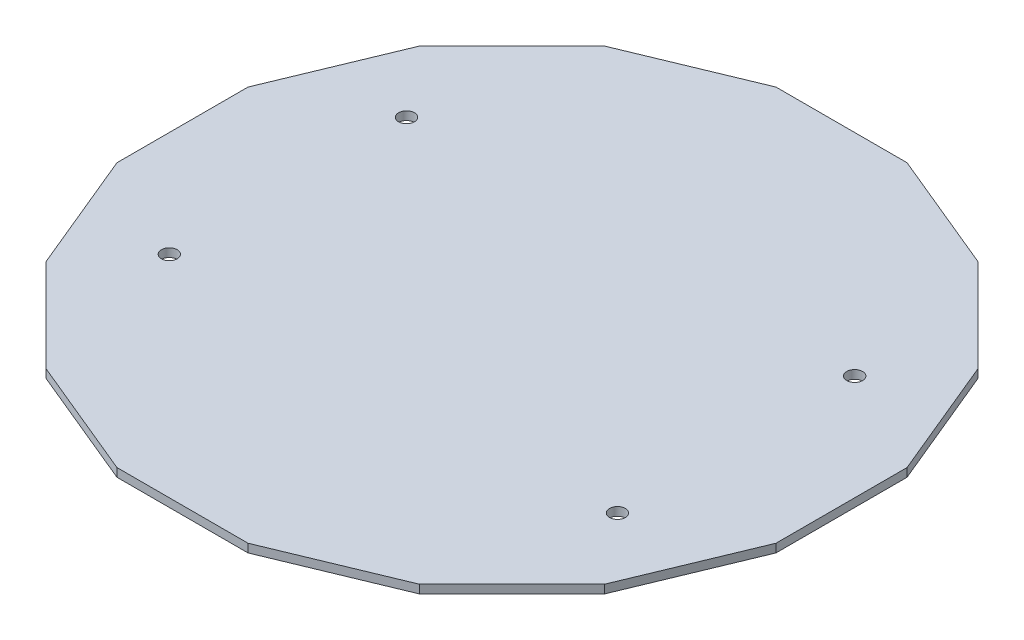
SolidWorks part; units mm, degrees
ref_plane "Front Plane" through (0, 0, 0) normal (0, 0, 1) x (1, 0, 0)
ref_plane "Top Plane" through (0, 0, 0) normal (0, 1, 0) x (1, 0, 0)
ref_plane "Right Plane" through (0, 0, 0) normal (1, 0, 0) x (0, 0, -1)
sketch "Sketch1" plane through (0, 0, 0) normal (0, 1, 0) x (1, 0, 0)
  line L1 (62.5, 12.432) -> (52.9849, 35.4034)
  line L2 (52.9849, 35.4034) -> (35.4034, 52.9849)
  line L3 (35.4034, 52.9849) -> (12.432, 62.5)
  line L4 (12.432, 62.5) -> (-12.432, 62.5)
  line L5 (-12.432, 62.5) -> (-35.4034, 52.9849)
  line L6 (-35.4034, 52.9849) -> (-52.9849, 35.4034)
  line L7 (-52.9849, 35.4034) -> (-62.5, 12.432)
  line L8 (-62.5, 12.432) -> (-62.5, -12.432)
  line L9 (-62.5, -12.432) -> (-52.9849, -35.4034)
  line L10 (-52.9849, -35.4034) -> (-35.4034, -52.9849)
  line L11 (-35.4034, -52.9849) -> (-12.432, -62.5)
  line L12 (-12.432, -62.5) -> (12.432, -62.5)
  line L13 (12.432, -62.5) -> (35.4034, -52.9849)
  line L14 (35.4034, -52.9849) -> (52.9849, -35.4034)
  line L15 (52.9849, -35.4034) -> (62.5, -12.432)
  line L16 (62.5, -12.432) -> (62.5, 12.432)
  circle A0 centre (0, 0) radius 62.5 construction
  dimension "D1" = 125
extrude "Boss-Extrude1" add sketch "Sketch1" along normal blind 1.6
sketch "Sketch2" plane through (0, 0, 0) normal (0, -1, 0) x (1, 0, 0)
  line L0 (-7.5, 62.5) -> (-3.3143, 51)
  line L1 (-12.432, 62.5) -> (12.432, 62.5) construction
  line L2 (-3.3143, 51) -> (3.3143, 51)
  line L3 (3.3143, 51) -> (7.5, 62.5)
  line L4 (7.5, 62.5) -> (9.0963, 62.5)
  line L5 (9.0963, 62.5) -> (4.3647, 49.5)
  line L6 (4.3647, 49.5) -> (-4.3647, 49.5)
  line L7 (-4.3647, 49.5) -> (-9.0963, 62.5)
  line L8 (-9.0963, 62.5) -> (-7.5, 62.5)
  line L131 (15.5139, 61.2235) -> (16.9886, 60.6126)
  line L132 (16.9886, 60.6126) -> (16.4548, 48.3862)
  line L133 (16.4548, 48.3862) -> (22.5789, 45.8495)
  line L134 (22.5789, 45.8495) -> (30.8468, 54.8723)
  line L135 (30.8468, 54.8723) -> (32.3216, 54.2615)
  line L136 (32.3216, 54.2615) -> (22.9752, 44.0618)
  line L137 (22.9752, 44.0618) -> (14.9104, 47.4023)
  line L138 (14.9104, 47.4023) -> (15.5139, 61.2235)
  line L139 (37.7621, 50.6262) -> (38.8909, 49.4975)
  line L140 (38.8909, 49.4975) -> (33.7189, 38.406)
  line L141 (33.7189, 38.406) -> (38.406, 33.7189)
  line L142 (38.406, 33.7189) -> (49.4975, 38.8909)
  line L143 (49.4975, 38.8909) -> (50.6262, 37.7621)
  line L144 (50.6262, 37.7621) -> (38.0881, 31.9155)
  line L145 (38.0881, 31.9155) -> (31.9155, 38.0881)
  line L146 (31.9155, 38.0881) -> (37.7621, 50.6262)
  line L147 (54.2615, 32.3216) -> (54.8723, 30.8468)
  line L148 (54.8723, 30.8468) -> (45.8495, 22.5789)
  line L149 (45.8495, 22.5789) -> (48.3862, 16.4548)
  line L150 (48.3862, 16.4548) -> (60.6126, 16.9886)
  line L151 (60.6126, 16.9886) -> (61.2235, 15.5139)
  line L152 (61.2235, 15.5139) -> (47.4023, 14.9104)
  line L153 (47.4023, 14.9104) -> (44.0618, 22.9752)
  line L154 (44.0618, 22.9752) -> (54.2615, 32.3216)
  line L155 (62.5, 9.0963) -> (62.5, 7.5)
  line L156 (62.5, 7.5) -> (51, 3.3143)
  line L157 (51, 3.3143) -> (51, -3.3143)
  line L158 (51, -3.3143) -> (62.5, -7.5)
  line L167 (62.5, -7.5) -> (62.5, -9.0963)
  line L184 (62.5, -9.0963) -> (49.5, -4.3647)
  line L185 (49.5, -4.3647) -> (49.5, 4.3647)
  line L186 (49.5, 4.3647) -> (62.5, 9.0963)
  line L187 (61.2235, -15.5139) -> (60.6126, -16.9886)
  line L188 (60.6126, -16.9886) -> (48.3862, -16.4548)
  line L189 (48.3862, -16.4548) -> (45.8495, -22.5789)
  line L190 (45.8495, -22.5789) -> (54.8723, -30.8468)
  line L191 (54.8723, -30.8468) -> (54.2615, -32.3216)
  line L192 (54.2615, -32.3216) -> (44.0618, -22.9752)
  line L193 (44.0618, -22.9752) -> (47.4023, -14.9104)
  line L194 (47.4023, -14.9104) -> (61.2235, -15.5139)
  line L195 (50.6262, -37.7621) -> (49.4975, -38.8909)
  line L196 (49.4975, -38.8909) -> (38.406, -33.7189)
  line L197 (38.406, -33.7189) -> (33.7189, -38.406)
  line L198 (33.7189, -38.406) -> (38.8909, -49.4975)
  line L199 (38.8909, -49.4975) -> (37.7621, -50.6262)
  line L200 (37.7621, -50.6262) -> (31.9155, -38.0881)
  line L201 (31.9155, -38.0881) -> (38.0881, -31.9155)
  line L202 (38.0881, -31.9155) -> (50.6262, -37.7621)
  line L203 (32.3216, -54.2615) -> (30.8468, -54.8723)
  line L204 (30.8468, -54.8723) -> (22.5789, -45.8495)
  line L205 (22.5789, -45.8495) -> (16.4548, -48.3862)
  line L206 (16.4548, -48.3862) -> (16.9886, -60.6126)
  line L207 (16.9886, -60.6126) -> (15.5139, -61.2235)
  line L208 (15.5139, -61.2235) -> (14.9104, -47.4023)
  line L209 (14.9104, -47.4023) -> (22.9752, -44.0618)
  line L210 (22.9752, -44.0618) -> (32.3216, -54.2615)
  line L211 (9.0963, -62.5) -> (7.5, -62.5)
  line L212 (7.5, -62.5) -> (3.3143, -51)
  line L213 (3.3143, -51) -> (-3.3143, -51)
  line L214 (-3.3143, -51) -> (-7.5, -62.5)
  line L215 (-7.5, -62.5) -> (-9.0963, -62.5)
  line L216 (-9.0963, -62.5) -> (-4.3647, -49.5)
  line L217 (-4.3647, -49.5) -> (4.3647, -49.5)
  line L218 (4.3647, -49.5) -> (9.0963, -62.5)
  line L219 (-15.5139, -61.2235) -> (-16.9886, -60.6126)
  line L220 (-16.9886, -60.6126) -> (-16.4548, -48.3862)
  line L221 (-16.4548, -48.3862) -> (-22.5789, -45.8495)
  line L222 (-22.5789, -45.8495) -> (-30.8468, -54.8723)
  line L223 (-30.8468, -54.8723) -> (-32.3216, -54.2615)
  line L224 (-32.3216, -54.2615) -> (-22.9752, -44.0618)
  line L225 (-22.9752, -44.0618) -> (-14.9104, -47.4023)
  line L226 (-14.9104, -47.4023) -> (-15.5139, -61.2235)
  line L227 (-37.7621, -50.6262) -> (-38.8909, -49.4975)
  line L228 (-38.8909, -49.4975) -> (-33.7189, -38.406)
  line L229 (-33.7189, -38.406) -> (-38.406, -33.7189)
  line L230 (-38.406, -33.7189) -> (-49.4975, -38.8909)
  line L231 (-49.4975, -38.8909) -> (-50.6262, -37.7621)
  line L232 (-50.6262, -37.7621) -> (-38.0881, -31.9155)
  line L233 (-38.0881, -31.9155) -> (-31.9155, -38.0881)
  line L234 (-31.9155, -38.0881) -> (-37.7621, -50.6262)
  line L235 (-54.2615, -32.3216) -> (-54.8723, -30.8468)
  line L236 (-54.8723, -30.8468) -> (-45.8495, -22.5789)
  line L237 (-45.8495, -22.5789) -> (-48.3862, -16.4548)
  line L238 (-48.3862, -16.4548) -> (-60.6126, -16.9886)
  line L239 (-60.6126, -16.9886) -> (-61.2235, -15.5139)
  line L240 (-61.2235, -15.5139) -> (-47.4023, -14.9104)
  line L241 (-47.4023, -14.9104) -> (-44.0618, -22.9752)
  line L242 (-44.0618, -22.9752) -> (-54.2615, -32.3216)
  line L243 (-62.5, -9.0963) -> (-62.5, -7.5)
  line L244 (-62.5, -7.5) -> (-51, -3.3143)
  line L245 (-51, -3.3143) -> (-51, 3.3143)
  line L246 (-51, 3.3143) -> (-62.5, 7.5)
  line L247 (-62.5, 7.5) -> (-62.5, 9.0963)
  line L248 (-62.5, 9.0963) -> (-49.5, 4.3647)
  line L249 (-49.5, 4.3647) -> (-49.5, -4.3647)
  line L250 (-49.5, -4.3647) -> (-62.5, -9.0963)
  line L251 (-61.2235, 15.5139) -> (-60.6126, 16.9886)
  line L252 (-60.6126, 16.9886) -> (-48.3862, 16.4548)
  line L253 (-48.3862, 16.4548) -> (-45.8495, 22.5789)
  line L254 (-45.8495, 22.5789) -> (-54.8723, 30.8468)
  line L255 (-54.8723, 30.8468) -> (-54.2615, 32.3216)
  line L256 (-54.2615, 32.3216) -> (-44.0618, 22.9752)
  line L257 (-44.0618, 22.9752) -> (-47.4023, 14.9104)
  line L258 (-47.4023, 14.9104) -> (-61.2235, 15.5139)
  line L259 (-50.6262, 37.7621) -> (-49.4975, 38.8909)
  line L260 (-49.4975, 38.8909) -> (-38.406, 33.7189)
  line L261 (-38.406, 33.7189) -> (-33.7189, 38.406)
  line L262 (-33.7189, 38.406) -> (-38.8909, 49.4975)
  line L263 (-38.8909, 49.4975) -> (-37.7621, 50.6262)
  line L264 (-37.7621, 50.6262) -> (-31.9155, 38.0881)
  line L265 (-31.9155, 38.0881) -> (-38.0881, 31.9155)
  line L266 (-38.0881, 31.9155) -> (-50.6262, 37.7621)
  line L267 (-32.3216, 54.2615) -> (-30.8468, 54.8723)
  line L268 (-30.8468, 54.8723) -> (-22.5789, 45.8495)
  line L269 (-22.5789, 45.8495) -> (-16.4548, 48.3862)
  line L270 (-16.4548, 48.3862) -> (-16.9886, 60.6126)
  line L271 (-16.9886, 60.6126) -> (-15.5139, 61.2235)
  line L272 (-15.5139, 61.2235) -> (-14.9104, 47.4023)
  line L273 (-14.9104, 47.4023) -> (-22.9752, 44.0618)
  line L274 (-22.9752, 44.0618) -> (-32.3216, 54.2615)
  point P4 (0, 51)
  point P11 (0, 49.5)
  point P136 (0, 0)
  point P138 (0, 0)
  dimension "D6" = 16
  dimension "D1" = 1.5
  dimension "D2" = 1.5
  dimension "D3" = 15
  dimension "D4" = 40
  dimension "D5" = 11.5
extrude "Boss-Extrude5" [suppressed] add sketch "Sketch2" along normal blind 6
sketch "Sketch6" plane through (0, 1.6, 0) normal (0, 1, 0) x (1, 0, 0)
  line L1 (-42.5, -22.5) -> (42.5, -22.5) construction
  line L2 (-42.5, -22.5) -> (-42.5, 22.5) construction
  line L3 (-42.5, 22.5) -> (42.5, 22.5) construction
  line L4 (42.5, -22.5) -> (42.5, 22.5) construction
  line L5 (-42.5, -22.5) -> (42.5, 22.5) construction
  line L6 (-42.5, 22.5) -> (42.5, -22.5) construction
  circle A0 centre (-42.5, 22.5) radius 1.5
  circle A1 centre (-42.5, -22.5) radius 1.5
  circle A2 centre (42.5, -22.5) radius 1.5
  circle A3 centre (42.5, 22.5) radius 1.5
  point P0 (0, 0)
  dimension "D3" = 3
  dimension "D1" = 85
  dimension "D2" = 45
extrude "Cut-Extrude2" cut sketch "Sketch6" against normal up to surface (1.6 mm away) up to face at (0, 0, 0)
sketch "Sketch17" [suppressed] plane through (0, -6, 0) normal (0, -1, 0) x (1, 0, 0)
  line L1 (-9.8462, 49.5) -> (-28.0395, 41.9641)
  line L2 (-28.0395, 41.9641) -> (-41.9641, 28.0395)
  line L3 (-41.9641, 28.0395) -> (-49.5, 9.8462)
  line L4 (-49.5, 9.8462) -> (-49.5, -9.8462)
  line L5 (-49.5, -9.8462) -> (-41.9641, -28.0395)
  line L6 (-41.9641, -28.0395) -> (-28.0395, -41.9641)
  line L7 (-28.0395, -41.9641) -> (-9.8462, -49.5)
  line L8 (-9.8462, -49.5) -> (9.8462, -49.5)
  line L9 (9.8462, -49.5) -> (28.0395, -41.9641)
  line L10 (28.0395, -41.9641) -> (41.9641, -28.0395)
  line L11 (41.9641, -28.0395) -> (49.5, -9.8462)
  line L12 (49.5, -9.8462) -> (49.5, 9.8462)
  line L13 (49.5, 9.8462) -> (41.9641, 28.0395)
  line L14 (41.9641, 28.0395) -> (28.0395, 41.9641)
  line L15 (28.0395, 41.9641) -> (9.8462, 49.5)
  line L16 (9.8462, 49.5) -> (-9.8462, 49.5)
  line L18 (-49.5, -4.3647) -> (-49.5, 4.3647) construction
  line L20 (-10.1445, 51) -> (-28.8892, 43.2357)
  line L21 (-28.8892, 43.2357) -> (-43.2357, 28.8892)
  line L22 (-43.2357, 28.8892) -> (-51, 10.1445)
  line L23 (-51, 10.1445) -> (-51, -10.1445)
  line L24 (-51, -10.1445) -> (-43.2357, -28.8892)
  line L25 (-43.2357, -28.8892) -> (-28.8892, -43.2357)
  line L26 (-28.8892, -43.2357) -> (-10.1445, -51)
  line L27 (-10.1445, -51) -> (10.1445, -51)
  line L28 (10.1445, -51) -> (28.8892, -43.2357)
  line L29 (28.8892, -43.2357) -> (43.2357, -28.8892)
  line L30 (43.2357, -28.8892) -> (51, -10.1445)
  line L31 (51, -10.1445) -> (51, 10.1445)
  line L32 (51, 10.1445) -> (43.2357, 28.8892)
  line L33 (43.2357, 28.8892) -> (28.8892, 43.2357)
  line L34 (28.8892, 43.2357) -> (10.1445, 51)
  line L35 (10.1445, 51) -> (-10.1445, 51)
  line L36 (-51, 3.3143) -> (-51, -3.3143) construction
  circle A0 centre (0, 0) radius 49.5 construction
  circle A1 centre (0, 0) radius 51 construction
extrude "Boss-Extrude9" [suppressed] add sketch "Sketch17" against normal up to surface (6 mm away)
sketch "Sketch16" [suppressed] plane through (0, -6, 0) normal (0, -1, 0) x (1, 0, 0)
  line L0 (-49.5, 9.8462) -> (-41.9641, 28.0395) construction
  line L1 (-43.8477, 19.2462) -> (-40.356, 19.7059)
  line L2 (-40.356, 19.7059) -> (-39.0083, 22.9597)
  line L3 (-39.0083, 22.9597) -> (-41.1523, 25.7538)
  line L4 (-41.1523, 25.7538) -> (-44.644, 25.2941)
  line L5 (-44.644, 25.2941) -> (-45.9917, 22.0403)
  line L6 (-45.9917, 22.0403) -> (-43.8477, 19.2462)
  line L7 (0, -0.88) -> (0, 0.88) construction
  line L8 (45.9917, 22.0403) -> (43.8477, 19.2462)
  line L9 (44.644, 25.2941) -> (45.9917, 22.0403)
  line L10 (41.1523, 25.7538) -> (44.644, 25.2941)
  line L11 (39.0083, 22.9597) -> (41.1523, 25.7538)
  line L12 (40.356, 19.7059) -> (39.0083, 22.9597)
  line L13 (43.8477, 19.2462) -> (40.356, 19.7059)
  line L14 (0.88, 0) -> (-0.88, 0) construction
  line L15 (44.644, -25.2941) -> (45.9917, -22.0403)
  line L16 (41.1523, -25.7538) -> (44.644, -25.2941)
  line L17 (39.0083, -22.9597) -> (41.1523, -25.7538)
  line L18 (40.356, -19.7059) -> (39.0083, -22.9597)
  line L19 (43.8477, -19.2462) -> (40.356, -19.7059)
  line L20 (45.9917, -22.0403) -> (43.8477, -19.2462)
  line L21 (-45.9917, -22.0403) -> (-43.8477, -19.2462)
  line L22 (-44.644, -25.2941) -> (-45.9917, -22.0403)
  line L23 (-41.1523, -25.7538) -> (-44.644, -25.2941)
  line L24 (-39.0083, -22.9597) -> (-41.1523, -25.7538)
  line L25 (-40.356, -19.7059) -> (-39.0083, -22.9597)
  line L26 (-43.8477, -19.2462) -> (-40.356, -19.7059)
  circle A0 centre (-42.5, 22.5) radius 3.05 construction
  dimension "D1" = 6.1
extrude "Cut-Extrude5" [suppressed] cut sketch "Sketch16" against normal up to surface (6 mm away)
sketch "Sketch21" [suppressed] plane through (0, 0, 0) normal (0, -1, 0) x (1, 0, 0)
  line L0 (-44.644, 25.2941) -> (-45.9917, 22.0403) construction
  line L1 (-47.1365, 21.8896) -> (-45.4317, 19.6678)
  line L5 (-42.5704, 26.5757) -> (-45.3469, 26.2101)
  line L6 (-45.3469, 26.2101) -> (-47.1365, 21.8896)
  line L7 (-45.9917, 22.0403) -> (-44.9898, 20.7347)
  line L11 (-43.0123, 25.5089) -> (-44.644, 25.2941)
  line L12 (-44.644, 25.2941) -> (-45.9917, 22.0403)
  line L13 (-43.0123, 25.5089) -> (-42.5704, 26.5757)
  line L15 (-43.0123, 25.5089) -> (-41.9641, 28.0395) construction
  line L16 (-44.9898, 20.7347) -> (-45.4317, 19.6678)
  line L17 (-49.5, 9.8462) -> (-44.9898, 20.7347) construction
  line L18 (0, -4.18) -> (0, 4.18) construction
  line L19 (-42.1019, 19.4761) -> (-40.356, 19.7059) [skipped]
  line L20 (-41.9714, 18.4846) -> (-39.6531, 18.7899) [skipped]
  line L21 (-38.7583, 20.9501) -> (-37.8635, 23.1104) [skipped]
  line L22 (-39.6822, 21.3328) -> (-39.0083, 22.9597) [skipped]
  line L23 (-39.0083, 22.9597) -> (-41.1523, 25.7538) [skipped]
  line L24 (-37.8635, 23.1104) -> (-40.7104, 26.8206) [skipped]
  line L25 (43.0123, 25.5089) -> (42.5704, 26.5757)
  line L26 (42.5704, 26.5757) -> (45.3469, 26.2101)
  line L27 (45.3469, 26.2101) -> (47.1365, 21.8896)
  line L28 (47.1365, 21.8896) -> (45.4317, 19.6678)
  line L29 (44.9898, 20.7347) -> (45.4317, 19.6678)
  line L30 (45.9917, 22.0403) -> (44.9898, 20.7347)
  line L31 (44.644, 25.2941) -> (45.9917, 22.0403)
  line L32 (43.0123, 25.5089) -> (44.644, 25.2941)
  line L33 (4.18, 0) -> (-4.18, 0) construction
  line L34 (43.0123, -25.5089) -> (44.644, -25.2941)
  line L35 (44.644, -25.2941) -> (45.9917, -22.0403)
  line L36 (45.9917, -22.0403) -> (44.9898, -20.7347)
  line L37 (44.9898, -20.7347) -> (45.4317, -19.6678)
  line L38 (47.1365, -21.8896) -> (45.4317, -19.6678)
  line L39 (45.3469, -26.2101) -> (47.1365, -21.8896)
  line L40 (42.5704, -26.5757) -> (45.3469, -26.2101)
  line L41 (43.0123, -25.5089) -> (42.5704, -26.5757)
  line L42 (-44.9898, -20.7347) -> (-45.4317, -19.6678)
  line L43 (-43.0123, -25.5089) -> (-42.5704, -26.5757)
  line L44 (-44.644, -25.2941) -> (-45.9917, -22.0403)
  line L45 (-43.0123, -25.5089) -> (-44.644, -25.2941)
  line L46 (-45.9917, -22.0403) -> (-44.9898, -20.7347)
  line L47 (-45.3469, -26.2101) -> (-47.1365, -21.8896)
  line L48 (-42.5704, -26.5757) -> (-45.3469, -26.2101)
  line L49 (-47.1365, -21.8896) -> (-45.4317, -19.6678)
  arc A0 (-42.5814, 26.5492) -> (-45.4208, 19.6943) centre (-42.5, 22.5) ccw construction
  arc A1 (-42.5814, -26.5492) -> (-45.4208, -19.6943) centre (-42.5, -22.5) cw construction
  dimension "D1" = 1
extrude "Boss-Extrude11" [suppressed] add sketch "Sketch21" along normal up to surface (6 mm away)
sketch "Sketch22" [suppressed] plane through (0, 0, 0) normal (0, -1, 0) x (1, 0, 0)
  line L0 (45.9917, 22.0403) -> (44.644, 25.2941) construction
  line L1 (44.644, 25.2941) -> (41.1523, 25.7538)
  line L2 (41.1523, 25.7538) -> (39.0083, 22.9597)
  line L3 (39.0083, 22.9597) -> (40.356, 19.7059)
  line L4 (40.356, 19.7059) -> (43.8477, 19.2462)
  line L5 (43.8477, 19.2462) -> (45.9917, 22.0403)
  line L6 (45.9917, 22.0403) -> (44.644, 25.2941)
  line L7 (0, -4.18) -> (0, 4.18) construction
  line L8 (-45.9917, 22.0403) -> (-44.644, 25.2941)
  line L9 (-43.8477, 19.2462) -> (-45.9917, 22.0403)
  line L10 (-40.356, 19.7059) -> (-43.8477, 19.2462)
  line L11 (-39.0083, 22.9597) -> (-40.356, 19.7059)
  line L12 (-41.1523, 25.7538) -> (-39.0083, 22.9597)
  line L13 (-44.644, 25.2941) -> (-41.1523, 25.7538)
  line L14 (4.18, 0) -> (-4.18, 0) construction
  line L15 (-44.644, -25.2941) -> (-41.1523, -25.7538)
  line L16 (-41.1523, -25.7538) -> (-39.0083, -22.9597)
  line L17 (-39.0083, -22.9597) -> (-40.356, -19.7059)
  line L18 (-40.356, -19.7059) -> (-43.8477, -19.2462)
  line L19 (-43.8477, -19.2462) -> (-45.9917, -22.0403)
  line L20 (-45.9917, -22.0403) -> (-44.644, -25.2941)
  line L21 (45.9917, -22.0403) -> (44.644, -25.2941)
  line L22 (43.8477, -19.2462) -> (45.9917, -22.0403)
  line L23 (40.356, -19.7059) -> (43.8477, -19.2462)
  line L24 (39.0083, -22.9597) -> (40.356, -19.7059)
  line L25 (41.1523, -25.7538) -> (39.0083, -22.9597)
  line L26 (44.644, -25.2941) -> (41.1523, -25.7538)
  circle A0 centre (42.5, 22.5) radius 3.05 construction
  circle A1 centre (42.5, 22.5) radius 1.5
  circle A2 centre (42.5, 22.5) radius 1.5 construction
  circle A3 centre (42.5, -22.5) radius 3.05 construction
  circle A4 centre (42.5, -22.5) radius 1.5
  circle A5 centre (-42.5, 22.5) radius 1.5
  circle A6 centre (-42.5, -22.5) radius 1.5
extrude "Boss-Extrude12" [suppressed] add sketch "Sketch22" along normal blind 2
sketch "Sketch23" [suppressed] plane through (0, -2, 0) normal (0, -1, 0) x (1, 0, 0)
  line L0 (-41.1523, 25.7538) -> (-42.2943, 27.2422)
  line L1 (-43.0123, 25.5089) -> (-41.9641, 28.0395) construction
  line L2 (-43.8477, 19.2462) -> (-45.7078, 19.0014)
  line L3 (-49.5, 9.8462) -> (-44.9898, 20.7347) construction
  line L4 (-43.8477, 19.2462) -> (-40.356, 19.7059) construction
  line L5 (-39.0083, 22.9597) -> (-41.1523, 25.7538) construction
  line L6 (-42.2943, 27.2422) -> (-43.0123, 25.5089)
  line L7 (-43.0123, 25.5089) -> (-41.1523, 25.7538)
  line L8 (-44.9898, 20.7347) -> (-43.8477, 19.2462)
  line L9 (-45.7078, 19.0014) -> (-44.9898, 20.7347)
  line L10 (4.18, 0) -> (-4.18, 0) construction
  line L11 (-43.8477, -19.2462) -> (-45.7078, -19.0014)
  line L12 (-44.9898, -20.7347) -> (-43.8477, -19.2462)
  line L13 (-45.7078, -19.0014) -> (-44.9898, -20.7347)
  line L14 (-42.2943, -27.2422) -> (-43.0123, -25.5089)
  line L15 (-41.1523, -25.7538) -> (-42.2943, -27.2422)
  line L16 (-43.0123, -25.5089) -> (-41.1523, -25.7538)
  line L17 (0, -4.18) -> (0, 4.18) construction
  line L18 (43.0123, -25.5089) -> (41.1523, -25.7538)
  line L19 (41.1523, -25.7538) -> (42.2943, -27.2422)
  line L20 (42.2943, -27.2422) -> (43.0123, -25.5089)
  line L21 (45.7078, -19.0014) -> (44.9898, -20.7347)
  line L22 (44.9898, -20.7347) -> (43.8477, -19.2462)
  line L23 (43.8477, -19.2462) -> (45.7078, -19.0014)
  line L24 (45.7078, 19.0014) -> (44.9898, 20.7347)
  line L25 (44.9898, 20.7347) -> (43.8477, 19.2462)
  line L26 (43.0123, 25.5089) -> (41.1523, 25.7538)
  line L27 (42.2943, 27.2422) -> (43.0123, 25.5089)
  line L28 (43.8477, 19.2462) -> (45.7078, 19.0014)
  line L29 (41.1523, 25.7538) -> (42.2943, 27.2422)
extrude "Boss-Extrude13" [suppressed] add sketch "Sketch23" against normal up to surface (2 mm away)
sketch "Sketch24" [suppressed] plane through (0, 0, 0) normal (0, -1, 0) x (1, 0, 0)
  line L0 (-12.432, 62.5) -> (-15.5139, 61.2235)
  line L1 (-15.5139, 61.2235) -> (-14.98, 48.9971)
  line L2 (-14.98, 48.9971) -> (-10.1445, 51)
  line L3 (-10.1445, 51) -> (-4.9106, 51)
  line L4 (-4.9106, 51) -> (-9.0963, 62.5)
  line L5 (-9.0963, 62.5) -> (-12.432, 62.5)
  line L6 (15.5139, 61.2235) -> (12.432, 62.5)
  line L7 (12.432, 62.5) -> (9.0963, 62.5)
  line L8 (9.0963, 62.5) -> (4.9106, 51)
  line L9 (4.9106, 51) -> (10.1445, 51)
  line L10 (10.1445, 51) -> (14.98, 48.9971)
  line L11 (14.98, 48.9971) -> (15.5139, 61.2235)
  line L12 (37.7621, 50.6262) -> (35.4034, 52.9849)
  line L13 (35.4034, 52.9849) -> (32.3216, 54.2615)
  line L14 (32.3216, 54.2615) -> (24.0537, 45.2386)
  line L15 (24.0537, 45.2386) -> (28.8892, 43.2357)
  line L16 (28.8892, 43.2357) -> (32.5901, 39.5348)
  line L17 (32.5901, 39.5348) -> (37.7621, 50.6262)
  line L18 (54.2615, 32.3216) -> (52.9849, 35.4034)
  line L19 (52.9849, 35.4034) -> (50.6262, 37.7621)
  line L20 (50.6262, 37.7621) -> (39.5348, 32.5901)
  line L21 (39.5348, 32.5901) -> (43.2357, 28.8892)
  line L22 (43.2357, 28.8892) -> (45.2386, 24.0537)
  line L23 (45.2386, 24.0537) -> (54.2615, 32.3216)
  line L24 (62.5, 9.0963) -> (62.5, 12.432)
  line L25 (62.5, 12.432) -> (61.2235, 15.5139)
  line L26 (61.2235, 15.5139) -> (48.9971, 14.98)
  line L27 (48.9971, 14.98) -> (51, 10.1445)
  line L28 (51, 10.1445) -> (51, 4.9106)
  line L29 (51, 4.9106) -> (62.5, 9.0963)
  line L30 (61.2235, -15.5139) -> (62.5, -12.432)
  line L31 (62.5, -12.432) -> (62.5, -9.0963)
  line L32 (62.5, -9.0963) -> (51, -4.9106)
  line L33 (51, -4.9106) -> (51, -10.1445)
  line L34 (51, -10.1445) -> (48.9971, -14.98)
  line L35 (48.9971, -14.98) -> (61.2235, -15.5139)
  line L36 (50.6262, -37.7621) -> (52.9849, -35.4034)
  line L37 (52.9849, -35.4034) -> (54.2615, -32.3216)
  line L38 (54.2615, -32.3216) -> (45.2386, -24.0537)
  line L39 (45.2386, -24.0537) -> (43.2357, -28.8892)
  line L40 (43.2357, -28.8892) -> (39.5348, -32.5901)
  line L41 (39.5348, -32.5901) -> (50.6262, -37.7621)
  line L42 (32.3216, -54.2615) -> (35.4034, -52.9849)
  line L43 (35.4034, -52.9849) -> (37.7621, -50.6262)
  line L44 (37.7621, -50.6262) -> (32.5901, -39.5348)
  line L45 (32.5901, -39.5348) -> (28.8892, -43.2357)
  line L46 (28.8892, -43.2357) -> (24.0537, -45.2386)
  line L47 (24.0537, -45.2386) -> (32.3216, -54.2615)
  line L48 (9.0963, -62.5) -> (12.432, -62.5)
  line L49 (12.432, -62.5) -> (15.5139, -61.2235)
  line L50 (15.5139, -61.2235) -> (14.98, -48.9971)
  line L51 (14.98, -48.9971) -> (10.1445, -51)
  line L52 (10.1445, -51) -> (4.9106, -51)
  line L53 (4.9106, -51) -> (9.0963, -62.5)
  line L54 (-15.5139, -61.2235) -> (-12.432, -62.5)
  line L55 (-12.432, -62.5) -> (-9.0963, -62.5)
  line L56 (-9.0963, -62.5) -> (-4.9106, -51)
  line L57 (-4.9106, -51) -> (-10.1445, -51)
  line L58 (-10.1445, -51) -> (-14.98, -48.9971)
  line L59 (-14.98, -48.9971) -> (-15.5139, -61.2235)
  line L60 (-37.7621, -50.6262) -> (-35.4034, -52.9849)
  line L61 (-35.4034, -52.9849) -> (-32.3216, -54.2615)
  line L62 (-32.3216, -54.2615) -> (-24.0537, -45.2386)
  line L63 (-24.0537, -45.2386) -> (-28.8892, -43.2357)
  line L64 (-28.8892, -43.2357) -> (-32.5901, -39.5348)
  line L65 (-32.5901, -39.5348) -> (-37.7621, -50.6262)
  line L66 (-54.2615, -32.3216) -> (-52.9849, -35.4034)
  line L67 (-52.9849, -35.4034) -> (-50.6262, -37.7621)
  line L68 (-50.6262, -37.7621) -> (-39.5348, -32.5901)
  line L69 (-39.5348, -32.5901) -> (-43.2357, -28.8892)
  line L70 (-43.2357, -28.8892) -> (-45.2386, -24.0537)
  line L71 (-45.2386, -24.0537) -> (-54.2615, -32.3216)
  line L72 (-62.5, -9.0963) -> (-62.5, -12.432)
  line L73 (-62.5, -12.432) -> (-61.2235, -15.5139)
  line L74 (-61.2235, -15.5139) -> (-48.9971, -14.98)
  line L75 (-48.9971, -14.98) -> (-51, -10.1445)
  line L76 (-51, -10.1445) -> (-51, -4.9106)
  line L77 (-51, -4.9106) -> (-62.5, -9.0963)
  line L78 (-61.2235, 15.5139) -> (-62.5, 12.432)
  line L79 (-62.5, 12.432) -> (-62.5, 9.0963)
  line L80 (-62.5, 9.0963) -> (-51, 4.9106)
  line L81 (-51, 4.9106) -> (-51, 10.1445)
  line L82 (-51, 10.1445) -> (-48.9971, 14.98)
  line L83 (-48.9971, 14.98) -> (-61.2235, 15.5139)
  line L84 (-50.6262, 37.7621) -> (-52.9849, 35.4034)
  line L85 (-52.9849, 35.4034) -> (-54.2615, 32.3216)
  line L86 (-54.2615, 32.3216) -> (-45.2386, 24.0537)
  line L87 (-45.2386, 24.0537) -> (-43.2357, 28.8892)
  line L88 (-43.2357, 28.8892) -> (-39.5348, 32.5901)
  line L89 (-39.5348, 32.5901) -> (-50.6262, 37.7621)
  line L90 (-32.3216, 54.2615) -> (-35.4034, 52.9849)
  line L91 (-35.4034, 52.9849) -> (-37.7621, 50.6262)
  line L92 (-37.7621, 50.6262) -> (-32.5901, 39.5348)
  line L93 (-32.5901, 39.5348) -> (-28.8892, 43.2357)
  line L94 (-28.8892, 43.2357) -> (-24.0537, 45.2386)
  line L95 (-24.0537, 45.2386) -> (-32.3216, 54.2615)
  point P104 (0, 0)
  dimension "D1" = 16
extrude "Boss-Extrude15" [suppressed] add sketch "Sketch24" along normal blind 1.5
sketch "Sketch18" plane through (0, 1.6, 0) normal (0, 1, 0) x (1, 0, 0)
  line L0 (-62.5, 12.432) -> (-62.5, -12.432) construction
  line L1 (-35.4034, 52.9849) -> (-52.9849, 35.4034)
  line L2 (-52.9849, 35.4034) -> (-62.5, 12.432)
  line L3 (-62.5, 12.432) -> (-62.5, -12.432)
  line L4 (-62.5, -12.432) -> (-52.9849, -35.4034)
  line L5 (-52.9849, -35.4034) -> (-35.4034, -52.9849)
  line L6 (-35.4034, -52.9849) -> (-12.432, -62.5)
  line L7 (-12.432, -62.5) -> (12.432, -62.5)
  line L8 (12.432, -62.5) -> (35.4034, -52.9849)
  line L9 (35.4034, -52.9849) -> (52.9849, -35.4034)
  line L10 (52.9849, -35.4034) -> (62.5, -12.432)
  line L11 (62.5, -12.432) -> (62.5, 12.432)
  line L12 (62.5, 12.432) -> (52.9849, 35.4034)
  line L13 (52.9849, 35.4034) -> (35.4034, 52.9849)
  line L14 (35.4034, 52.9849) -> (12.432, 62.5)
  line L15 (12.432, 62.5) -> (-12.432, 62.5)
  line L16 (-12.432, 62.5) -> (-35.4034, 52.9849)
  circle A0 centre (0, 0) radius 62.5 construction
extrude "Cut-Extrude6" [suppressed] cut sketch "Sketch18" against normal up to surface (1.6 mm away)
sketch "Sketch25" plane through (0, 1.6, 0) normal (0, 1, 0) x (1, 0, 0)
  line L0 (0, 62.5) -> (21.8382, 122.5)
  line L1 (12.432, 62.5) -> (-12.432, 62.5) construction
  line L2 (21.8382, 122.5) -> (-21.8382, 122.5)
  line L3 (-21.8382, 122.5) -> (0, 62.5)
  line L4 (26.7028, 121.5324) -> (23.9177, 57.7425)
  line L5 (23.9177, 57.7425) -> (67.0546, 104.8181)
  line L6 (67.0546, 104.8181) -> (26.7028, 121.5324)
  line L7 (71.1786, 102.0625) -> (44.1942, 44.1942)
  line L8 (44.1942, 44.1942) -> (102.0625, 71.1786)
  line L9 (102.0625, 71.1786) -> (71.1786, 102.0625)
  line L10 (104.8181, 67.0546) -> (57.7425, 23.9177)
  line L11 (57.7425, 23.9177) -> (121.5324, 26.7028)
  line L12 (121.5324, 26.7028) -> (104.8181, 67.0546)
  line L13 (122.5, 21.8382) -> (62.5, 0)
  line L14 (62.5, 0) -> (122.5, -21.8382)
  line L15 (122.5, -21.8382) -> (122.5, 21.8382)
  line L16 (121.5324, -26.7028) -> (57.7425, -23.9177)
  line L17 (57.7425, -23.9177) -> (104.8181, -67.0546)
  line L18 (104.8181, -67.0546) -> (121.5324, -26.7028)
  line L19 (102.0625, -71.1786) -> (44.1942, -44.1942)
  line L20 (44.1942, -44.1942) -> (71.1786, -102.0625)
  line L21 (71.1786, -102.0625) -> (102.0625, -71.1786)
  line L22 (67.0546, -104.8181) -> (23.9177, -57.7425)
  line L23 (23.9177, -57.7425) -> (26.7028, -121.5324)
  line L24 (26.7028, -121.5324) -> (67.0546, -104.8181)
  line L25 (21.8382, -122.5) -> (0, -62.5)
  line L26 (0, -62.5) -> (-21.8382, -122.5)
  line L27 (-21.8382, -122.5) -> (21.8382, -122.5)
  line L28 (-26.7028, -121.5324) -> (-23.9177, -57.7425)
  line L29 (-23.9177, -57.7425) -> (-67.0546, -104.8181)
  line L30 (-67.0546, -104.8181) -> (-26.7028, -121.5324)
  line L31 (-71.1786, -102.0625) -> (-44.1942, -44.1942)
  line L32 (-44.1942, -44.1942) -> (-102.0625, -71.1786)
  line L33 (-102.0625, -71.1786) -> (-71.1786, -102.0625)
  line L34 (-104.8181, -67.0546) -> (-57.7425, -23.9177)
  line L35 (-57.7425, -23.9177) -> (-121.5324, -26.7028)
  line L36 (-121.5324, -26.7028) -> (-104.8181, -67.0546)
  line L37 (-122.5, -21.8382) -> (-62.5, 0)
  line L38 (-62.5, 0) -> (-122.5, 21.8382)
  line L39 (-122.5, 21.8382) -> (-122.5, -21.8382)
  line L40 (-121.5324, 26.7028) -> (-57.7425, 23.9177)
  line L41 (-57.7425, 23.9177) -> (-104.8181, 67.0546)
  line L42 (-104.8181, 67.0546) -> (-121.5324, 26.7028)
  line L43 (-102.0625, 71.1786) -> (-44.1942, 44.1942)
  line L44 (-44.1942, 44.1942) -> (-71.1786, 102.0625)
  line L45 (-71.1786, 102.0625) -> (-102.0625, 71.1786)
  line L46 (-67.0546, 104.8181) -> (-23.9177, 57.7425)
  line L47 (-23.9177, 57.7425) -> (-26.7028, 121.5324)
  line L48 (-26.7028, 121.5324) -> (-67.0546, 104.8181)
  point P4 (0, 122.5)
  point P6 (0, 0)
  point P54 (0, 0)
  dimension "D1" = 40
  dimension "60" = 60
  dimension "D3" = 16
extrude "Boss-Extrude16" [suppressed] add sketch "Sketch25" along normal blind 2 separate body
sketch "Sketch26" plane through (0, 1.6, 0) normal (0, 1, 0) x (1, 0, 0)
  line L0 (0, 62.5) -> (-50, 112.5)
  line L1 (-50, 112.5) -> (50, 112.5)
  line L2 (50, 112.5) -> (0, 62.5)
  point P3 (0, 112.5)
  dimension "D1" = 50
  dimension "D2" = 90
extrude "Boss-Extrude17" [suppressed] add sketch "Sketch26" against normal blind 2
pattern_circular "CirPattern1" [suppressed] count 16 over 360
